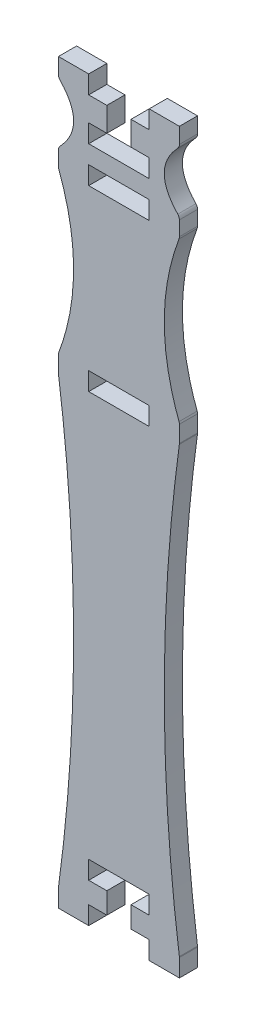
SolidWorks part; units mm, degrees
ref_plane "Alzado" through (0, 0, 0) normal (0, 0, 1) x (1, 0, 0)
ref_plane "Planta" through (0, 0, 0) normal (0, 1, 0) x (1, 0, 0)
ref_plane "Vista lateral" through (0, 0, 0) normal (1, 0, 0) x (0, 0, -1)
sketch "Croquis1" plane through (0, 0, 0) normal (0, 0, 1) x (1, 0, 0)
  line L0 (-0.5, 63) -> (0, 63)
  line L1 (-10, 70) -> (-10, 67)
  line L2 (-7, 67) -> (-10, 67)
  line L3 (0, 63) -> (0, 60)
  line L4 (-15, 70) -> (-15, 67.4057)
  line L5 (0, 60) -> (-0.5, 60)
  line L6 (-7, -45.5) -> (-7, -49)
  line L7 (-0.5, -42.5) -> (-9.5, -42.5)
  line L8 (-9.5, 63) -> (-10, 63)
  line L9 (-10, 70) -> (-15, 70)
  line L10 (-9.5, 60) -> (-0.5, 60)
  line L11 (-10, -52) -> (-10, -49)
  line L12 (-10, -52) -> (-15, -52)
  line L14 (-0.5, -45.5) -> (-3, -45.5)
  line L15 (-15, -52) -> (-15, -51.7014)
  line L16 (0, -49) -> (0, -52)
  line L17 (-0.5, -45.5) -> (0, -45.5)
  line L18 (-3, -45.5) -> (-3, -49)
  line L19 (-0.5, 63) -> (-3, 63)
  line L20 (-10, 27.5) -> (-10, 24.5)
  line L21 (-3, 63) -> (-3, 67)
  line L22 (-10, 24.5) -> (0, 24.5)
  line L23 (0, 24.5) -> (0, 27.5)
  line L24 (-7, 63) -> (-7, 67)
  line L25 (-15, 27.3187) -> (-15, 24.5677)
  line L26 (-9.5, -45.5) -> (-7, -45.5)
  line L28 (-7, -49) -> (-10, -49)
  line L29 (-9.5, 63) -> (-7, 63)
  line L30 (0, -45.5) -> (0, -42.5)
  line L31 (-10, 54) -> (-10, 57)
  line L32 (-10, 54) -> (0, 54)
  line L33 (-10, 57) -> (0, 57)
  line L34 (0, 57) -> (0, 54)
  line L35 (-3, 67) -> (0, 67)
  line L36 (0, -52) -> (5, -52)
  line L37 (0, 67) -> (0, 70)
  line L38 (5, 70) -> (0, 70)
  line L39 (5, -52) -> (5, -51.7014)
  line L40 (0, 27.5) -> (-10, 27.5)
  line L41 (-10, 63) -> (-10, 60)
  line L42 (-15, 56.5943) -> (-15, 54.1813)
  line L43 (0, -49) -> (-3, -49)
  line L44 (-10, 60) -> (-9.5, 60)
  line L45 (0, -42.5) -> (-0.5, -42.5)
  line L46 (-15, -49.0677) -> (-15, -51.7014)
  line L47 (-9.5, -45.5) -> (-10, -45.5)
  line L48 (-10, -45.5) -> (-10, -42.5)
  line L49 (-10, -42.5) -> (-9.5, -42.5)
  line L51 (5, -51.7014) -> (5, -49.0677)
  line L53 (5, 24.5677) -> (5, 27.3187)
  line L55 (5, 54.1813) -> (5, 56.5943)
  line L57 (5, 67.4057) -> (5, 70)
  arc A4 (-14.9909, -48.9331) -> (-15, -49.0677) centre (-14, -49.0677) ccw
  arc A5 (5, -49.0677) -> (4.9909, -48.9331) centre (4, -49.0677) ccw
  arc A6 (-15, 24.5677) -> (-14.9909, 24.4331) centre (-14, 24.5677) ccw
  arc A7 (4.9909, 24.4331) -> (5, 24.5677) centre (4, 24.5677) ccw
  arc A8 (-14.9371, 27.6678) -> (-15, 27.3187) centre (-14, 27.3187) ccw
  arc A9 (5, 27.3187) -> (4.9371, 27.6678) centre (4, 27.3187) ccw
  arc A10 (-14.7272, 57.2807) -> (-15, 56.5943) centre (-14, 56.5943) ccw
  arc A11 (-15, 54.1813) -> (-14.9371, 53.8322) centre (-14, 54.1813) ccw
  arc A12 (4.9371, 53.8322) -> (5, 54.1813) centre (4, 54.1813) ccw
  arc A13 (5, 56.5943) -> (4.7272, 57.2807) centre (4, 56.5943) ccw
  arc A14 (4.7272, 66.7193) -> (5, 67.4057) centre (4, 67.4057) ccw
  arc A15 (-15, 67.4057) -> (-14.7272, 66.7193) centre (-14, 67.4057) ccw
  spline S0 degree 3 poles (4.7272, 66.7193) (3.2424, 65.1462) (1.7576, 62) (3.2424, 58.8538) (4.7272, 57.2807) knots 0.028065 0.028065 0.028065 0.028065 0.5 0.971935 0.971935 0.971935 0.971935
  spline S1 degree 3 poles (-14.7272, 57.2807) (-13.2424, 58.8538) (-11.7576, 62) (-13.2424, 65.1462) (-14.7272, 66.7193) knots 0.028065 0.028065 0.028065 0.028065 0.5 0.971935 0.971935 0.971935 0.971935
  spline S2 degree 3 poles (-14.9371, 53.8322) (-13.3124, 49.4715) (-11.6876, 40.75) (-13.3124, 32.0285) (-14.9371, 27.6678) knots 0.006333 0.006333 0.006333 0.006333 0.5 0.993667 0.993667 0.993667 0.993667
  spline S3 degree 3 poles (4.9371, 53.8322) (3.3124, 49.4715) (1.6876, 40.75) (3.3124, 32.0285) (4.9371, 27.6678) knots 0.006333 0.006333 0.006333 0.006333 0.5 0.993667 0.993667 0.993667 0.993667
  spline S4 degree 3 poles (-14.9909, -48.9331) (-13.3303, -36.7054) (-11.6697, -12.25) (-13.3303, 12.2054) (-14.9909, 24.4331) knots 0.00091 0.00091 0.00091 0.00091 0.5 0.99909 0.99909 0.99909 0.99909
  spline S7 degree 3 poles (4.9909, -48.9331) (3.3303, -36.7054) (1.6697, -12.25) (3.3303, 12.2054) (4.9909, 24.4331) knots 0.00091 0.00091 0.00091 0.00091 0.5 0.99909 0.99909 0.99909 0.99909
extrude "Saliente-Extruir1" add sketch "Croquis1" along normal blind 3
